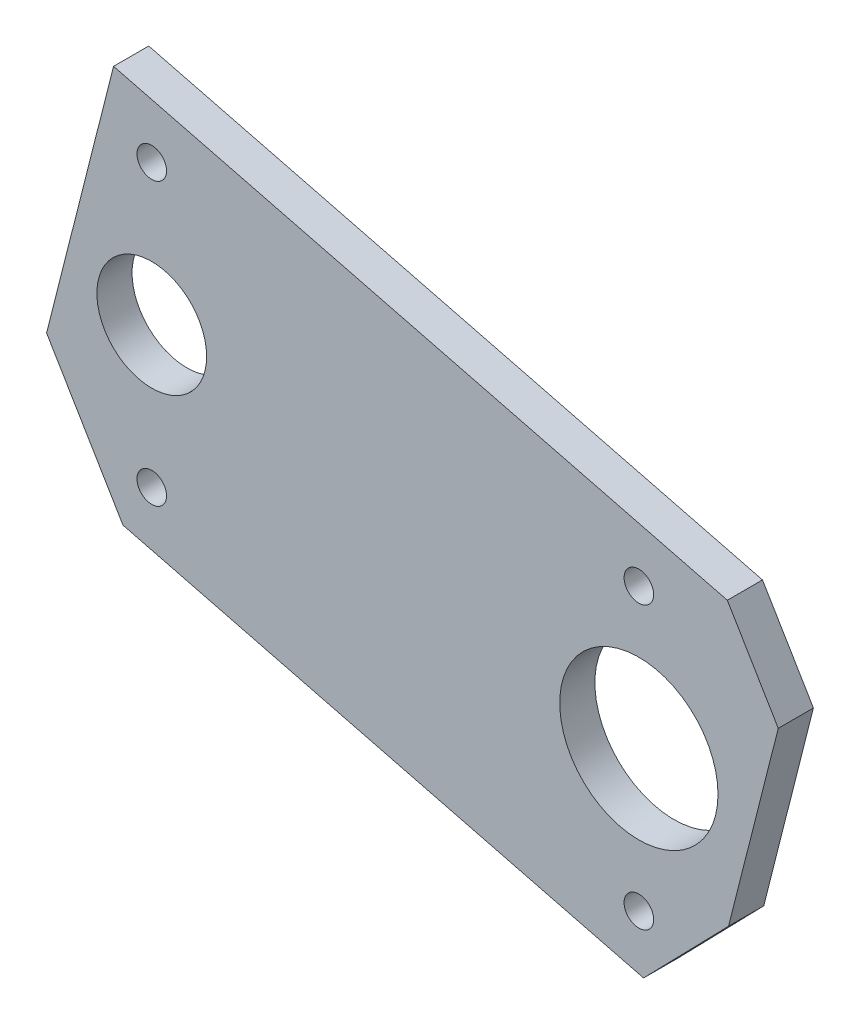
SolidWorks part; units mm, degrees
ref_plane "Front Plane" through (0, 0, 0) normal (0, 0, 1) x (1, 0, 0)
ref_plane "Top Plane" through (0, 0, 0) normal (0, 1, 0) x (1, 0, 0)
ref_plane "Right Plane" through (0, 0, 0) normal (1, 0, 0) x (0, 0, -1)
sketch "Sketch1" plane through (0, 0, 0) normal (0, 0, 1) x (1, 0, 0)
  line L0 (106.9816, 57.15) -> (106.9816, 31.75) construction
  line L1 (0, 0) -> (113.3316, 0) construction
  line L2 (0, 0) -> (0, 76.2) construction
  line L3 (0, 76.2) -> (113.3316, 76.2) construction
  line L4 (132.3816, 19.05) -> (132.3816, 57.15) construction
  line L5 (106.9816, 31.75) -> (106.9816, 6.35) construction
  line L6 (106.9816, 31.75) -> (17.0656, 31.75) construction
  line L7 (19.05, 79.4275) -> (19.05, 54.0275) construction
  line L8 (19.05, 54.0275) -> (19.05, 28.6275) construction
  line L9 (106.9816, 31.75) -> (19.05, 54.0275) construction
  line L10 (17.0656, 31.75) -> (17.0656, 89.7562) construction
  line L11 (19.4469, 31.75) -> (19.4469, 89.1529) construction
  line L12 (12.156, 91.0001) -> (122.9554, 62.929)
  line L13 (132.1474, 47.4989) -> (123.1725, 12.074)
  line L14 (107.8323, -3.6914) -> (13.8501, 20.119)
  line L15 (0.062, 43.2641) -> (12.156, 91.0001)
  line L16 (113.3316, 76.2) -> (132.3816, 57.15) construction
  line L17 (113.3316, 0) -> (132.3816, 19.05) construction
  line L18 (123.1725, 12.074) -> (107.8323, -3.6914)
  line L19 (122.9554, 62.929) -> (132.1474, 47.4989)
  line L20 (13.8501, 20.119) -> (0.062, 43.2641)
  circle A0 centre (19.05, 54.0275) radius 9.906
  circle A1 centre (106.9816, 31.75) radius 14.2875
  circle A2 centre (106.9816, 57.15) radius 2.667
  circle A3 centre (106.9816, 6.35) radius 2.667
  circle A4 centre (19.05, 79.4275) radius 2.667
  circle A5 centre (19.05, 28.6275) radius 2.667
  circle A6 centre (106.9816, 6.35) radius 6.35 construction
  point P1 (132.3816, 76.2)
  point P3 (132.3816, 0)
  point P22 (135.2664, 59.81)
  point P24 (118.494, -6.3926)
  point P25 (-4.6165, 24.7975)
  dimension "D4" = 5.334
  dimension "D5" = 19.812
  dimension "D6" = 28.575
  dimension "D11" = 25.4
  dimension "D12" = 19.05
  dimension "D18" = 12.7
  dimension "D2" = 90.7097
  dimension "D3" = 25.4
  dimension "D7" = 89.916
  dimension "D8" = 2.3813
  dimension "D9" = 0.3969
  dimension "D10" = 6.35
  dimension "D13" = 127
  dimension "D14" = 9.525
  dimension "D15" = 9.525
  dimension "D16" = 9.525
  dimension "D17" = 76.2
  dimension "D19" = 19.05
  dimension "D21" = 30
  dimension "D22" = 12.7
  dimension "D23" = 45
  dimension "D24" = 19.05
  dimension "D25" = 45
extrude "Boss-Extrude1" add sketch "Sketch1" along normal blind 6.35
